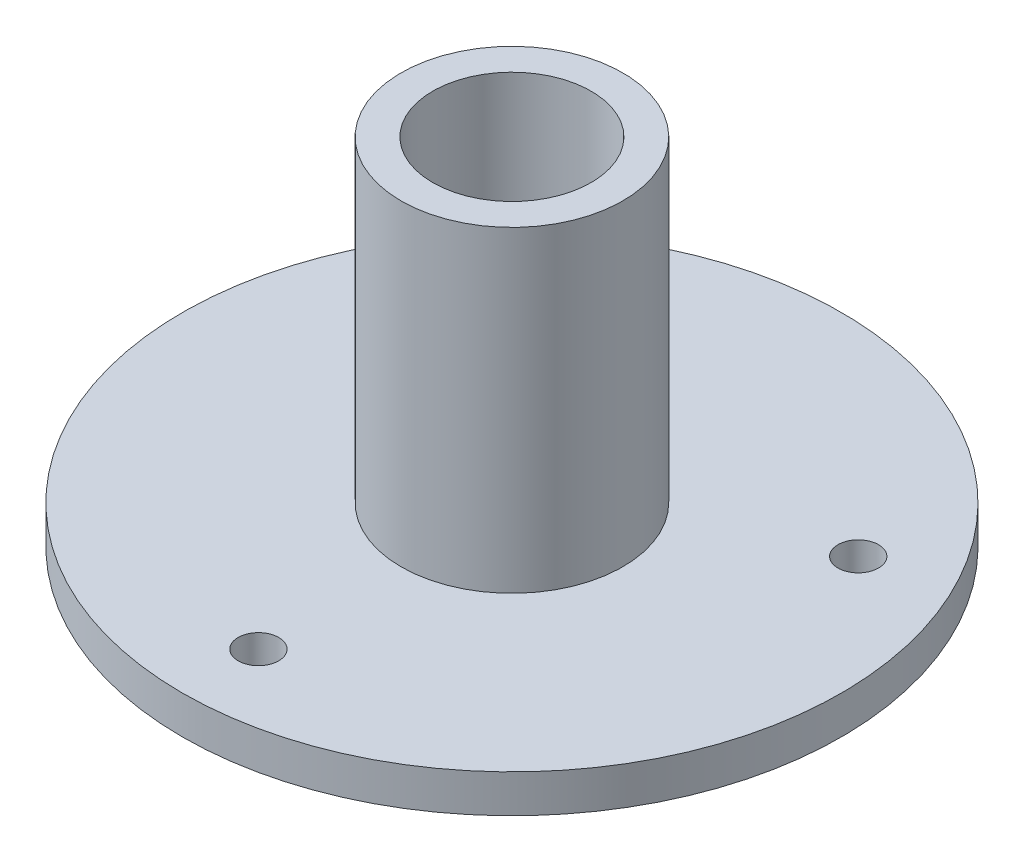
SolidWorks part; units mm, degrees
ref_plane "前视基准面" through (0, 0, 0) normal (0, 0, 1) x (1, 0, 0)
ref_plane "上视基准面" through (0, 0, 0) normal (0, 1, 0) x (1, 0, 0)
ref_plane "右视基准面" through (0, 0, 0) normal (1, 0, 0) x (0, 0, -1)
other "Configuration Table"
sketch "草图1" plane through (0, 0, 0) normal (0, 1, 0) x (1, 0, 0)
  circle A0 centre (0, 0) radius 26
  dimension "D1" = 52
extrude "凸台-拉伸1" add sketch "草图1" along normal blind 3
sketch "草图2" plane through (0, 3, 0) normal (0, 1, 0) x (1, 0, 0)
  circle A0 centre (0, 0) radius 8.75
  dimension "D1" = 17.5
extrude "凸台-拉伸2" add sketch "草图2" along normal blind 25
sketch "草图3" plane through (0, 28, 0) normal (0, 1, 0) x (1, 0, 0)
  circle A0 centre (0, 0) radius 6.25
  dimension "D1" = 12.5
extrude "切除-拉伸1" cut sketch "草图3" against normal up to surface (28 mm away) up to face at (0, 0, 26)
sketch "草图5" plane through (0, 0, 0) normal (0, -1, 0) x (1, 0, 0)
  circle A0 centre (0, 20) radius 1.6
  circle A1 centre (0, 0) radius 6.25 construction
  circle A2 centre (17.3205, -10) radius 1.6
  circle A3 centre (-17.3205, -10) radius 1.6
  point P11 (0, 0)
  dimension "D1" = 3.2
  dimension "D2" = 20
  dimension "D3" = 3
extrude "切除-拉伸3" cut sketch "草图5" against normal up to surface (3 mm away) up to face at (0, 3, 8.75)
